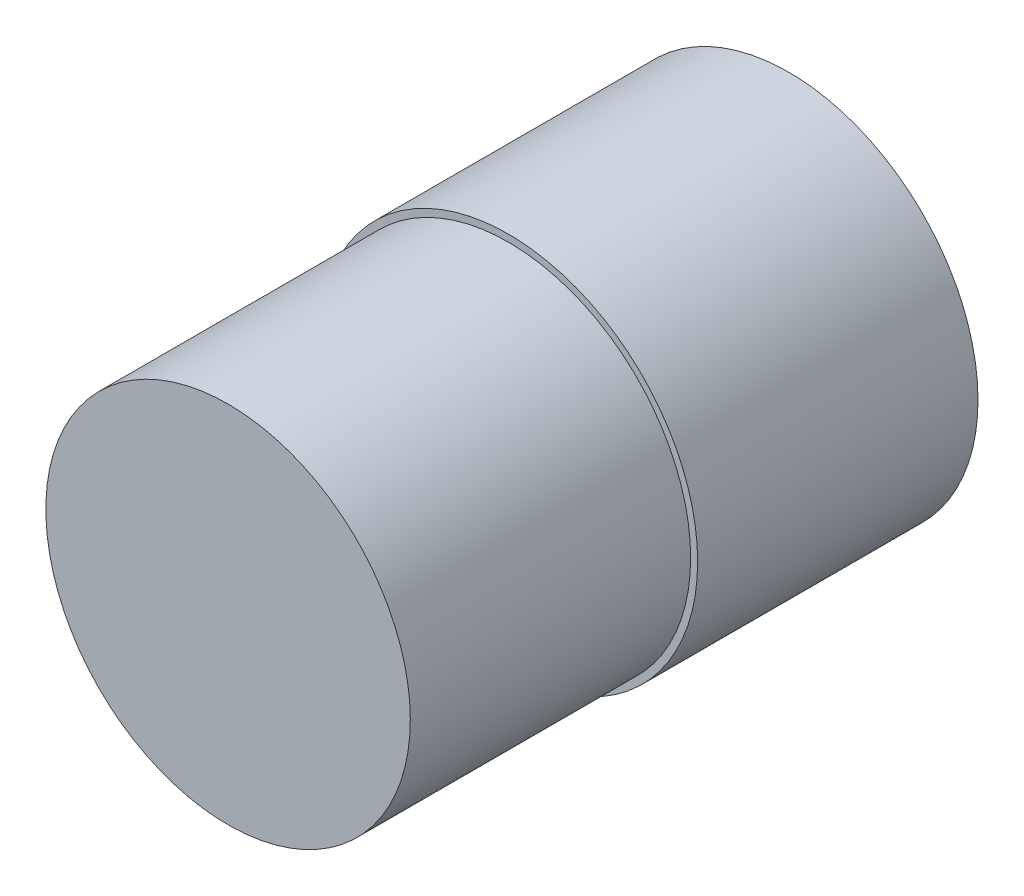
SolidWorks part; units mm, degrees
ref_plane "Front Plane" through (0, 0, 0) normal (0, 0, 1) x (1, 0, 0)
ref_plane "Top Plane" through (0, 0, 0) normal (0, 1, 0) x (1, 0, 0)
ref_plane "Right Plane" through (0, 0, 0) normal (1, 0, 0) x (0, 0, -1)
sketch "Sketch1" plane through (0, 0, 0) normal (0, 0, 1) x (1, 0, 0)
  circle A0 centre (0, 0) radius 6.75
  circle A1 centre (0, 0) radius 2.725
  dimension "D1" = 5.45
  dimension "D2" = 13.5
extrude "Boss-Extrude2" add sketch "Sketch1" along normal blind 10
sketch "Sketch2" plane through (0, 0, 10) normal (0, 0, 1) x (1, 0, 0)
  circle A0 centre (0, 0) radius 6.6
  dimension "D1" = 13.2
extrude "Boss-Extrude3" add sketch "Sketch2" along normal blind 10
sketch "Sketch3" plane through (0, 0, 20) normal (0, 0, 1) x (1, 0, 0)
  circle A0 centre (0, 0) radius 6.5
  circle A1 centre (0, 0) radius 6.5
  circle A2 centre (0, 0) radius 6.6 construction
  circle M1 centre (0, 0) radius 6.6
  dimension "D1" = 13
  dimension "D2" = 0.1
extrude "Cut-Extrude1" cut sketch "Sketch3" against normal blind 10 contours A0 M1
